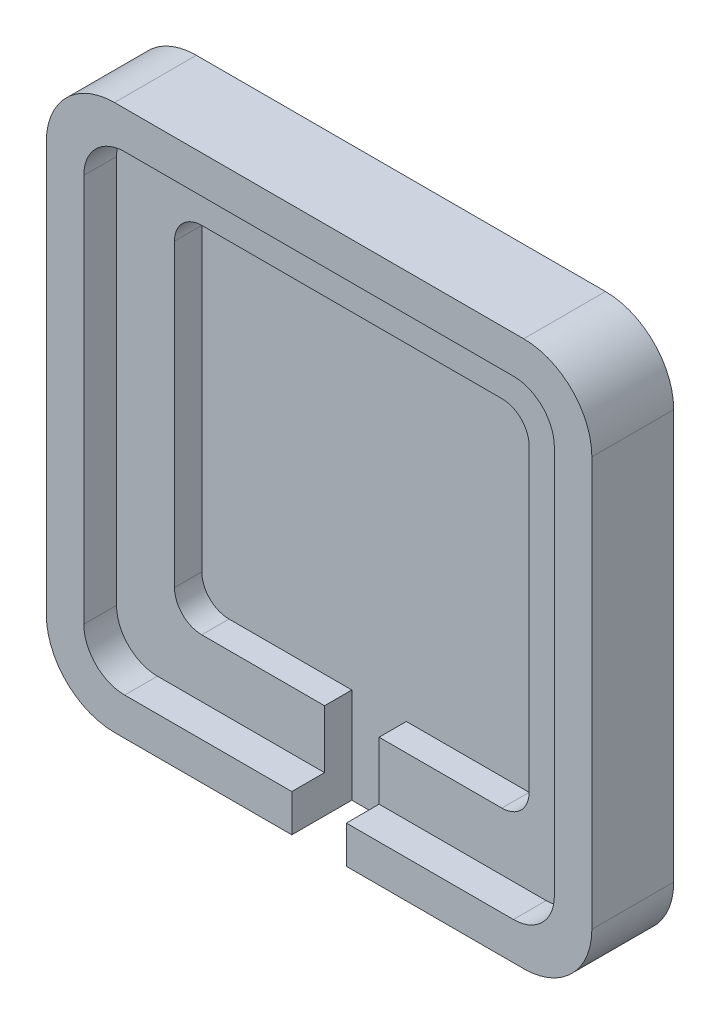
SolidWorks part; units mm, degrees
ref_plane "Ebene vorne" through (0, 0, 0) normal (0, 0, 1) x (1, 0, 0)
ref_plane "Ebene oben" through (0, 0, 0) normal (0, 1, 0) x (1, 0, 0)
ref_plane "Ebene rechts" through (0, 0, 0) normal (1, 0, 0) x (0, 0, -1)
sketch "Skizze1" plane through (0, 0, 0) normal (0, 0, 1) x (1, 0, 0)
  line L1 (20, -20) -> (-20, -20)
  line L2 (20, -20) -> (20, 20)
  line L3 (20, 20) -> (-20, 20)
  line L4 (-20, -20) -> (-20, 20)
  line L5 (20, -20) -> (-20, 20) construction
  line L6 (20, 20) -> (-20, -20) construction
  point P0 (0, 0)
  dimension "D1" = 40
  dimension "D2" = 40
extrude "Aufsatz-Linear austragen1" add sketch "Skizze1" along normal blind 6
fillet "Verrundung1" radius 5 4 edges at (-20, -20, 3) (-20, 20, 3) (20, 20, 3) (20, -20, 3)
sketch "Skizze2" plane through (0, 0, 6) normal (0, 0, 1) x (1, 0, 0)
  line L1 (17.25, -17.25) -> (-17.25, -17.25)
  line L2 (17.25, -17.25) -> (17.25, 17.25)
  line L3 (17.25, 17.25) -> (-17.25, 17.25)
  line L4 (-17.25, -17.25) -> (-17.25, 17.25)
  line L5 (17.25, -17.25) -> (-17.25, 17.25) construction
  line L6 (17.25, 17.25) -> (-17.25, -17.25) construction
  point P0 (0, 0)
  dimension "D1" = 34.5
  dimension "D2" = 34.5
extrude "Schnitt-Linear austragen1" cut sketch "Skizze2" against normal blind 2.4
fillet "Verrundung2" radius 3 4 edges at (17.25, 17.25, 4.8) (17.25, -17.25, 4.8) (-17.25, -17.25, 4.8) (-17.25, 17.25, 4.8)
sketch "Skizze3" plane through (0, 0, 3.6) normal (0, 0, 1) x (1, 0, 0)
  line L1 (-13, -13) -> (13, -13)
  line L2 (-13, -13) -> (-13, 13)
  line L3 (-13, 13) -> (13, 13)
  line L4 (13, -13) -> (13, 13)
  line L5 (-13, -13) -> (13, 13) construction
  line L6 (-13, 13) -> (13, -13) construction
  point P0 (0, 0)
  dimension "D1" = 26
  dimension "D2" = 26
extrude "Schnitt-Linear austragen2" cut sketch "Skizze3" against normal blind 2
fillet "Verrundung3" radius 2 4 edges at (13, -13, 2.6) (-13, -13, 2.6) (-13, 13, 2.6) (13, 13, 2.6)
sketch "Skizze4" plane through (0, 0, 6) normal (0, 0, 1) x (1, 0, 0)
  line L0 (0, 0) -> (0, -17.2969) construction
  line L1 (2, -12.2775) -> (-2, -12.2775)
  line L2 (2, -12.2775) -> (2, -22.3164)
  line L3 (2, -22.3164) -> (-2, -22.3164)
  line L4 (-2, -12.2775) -> (-2, -22.3164)
  line L5 (2, -12.2775) -> (-2, -22.3164) construction
  line L6 (2, -22.3164) -> (-2, -12.2775) construction
  point P0 (0, -17.2969)
  dimension "D1" = 4
extrude "Schnitt-Linear austragen3" cut sketch "Skizze4" against normal up to surface (4.4 mm away) up to face at (0, 0, 1.6)
